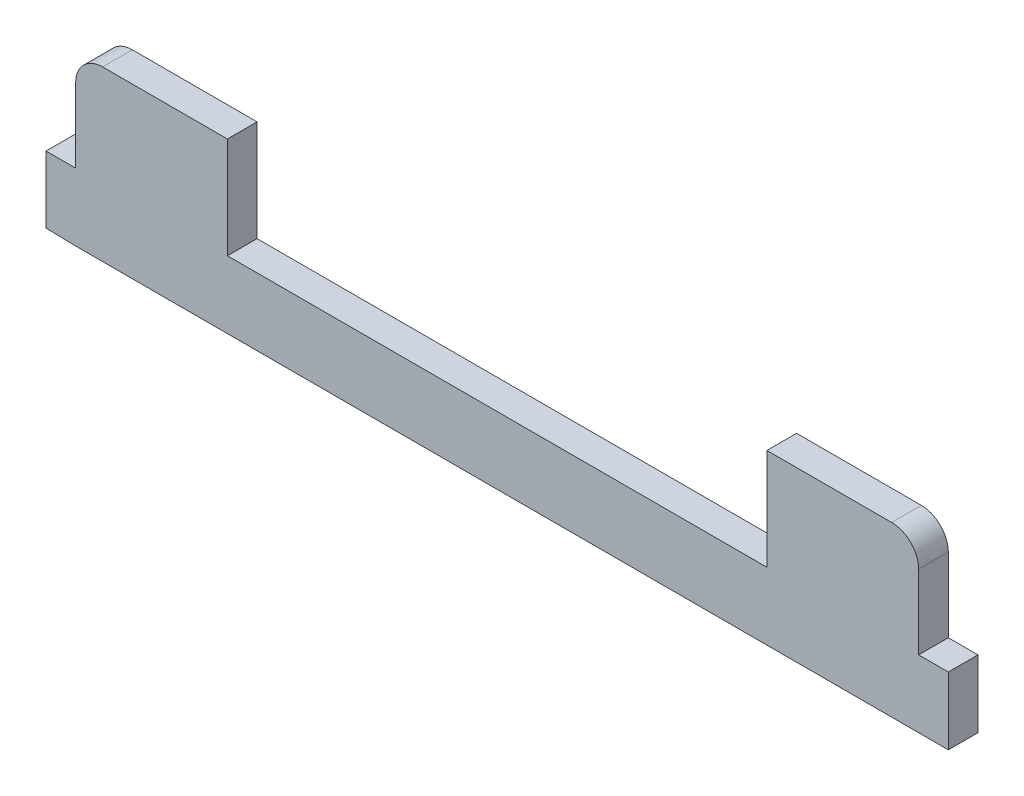
SolidWorks part; units mm, degrees
ref_plane "Front Plane" through (0, 0, 0) normal (0, 0, 1) x (1, 0, 0)
ref_plane "Top Plane" through (0, 0, 0) normal (0, 1, 0) x (1, 0, 0)
ref_plane "Right Plane" through (0, 0, 0) normal (1, 0, 0) x (0, 0, -1)
sketch "Sketch1" plane through (0, 0, 0) normal (0, 0, 1) x (1, 0, 0)
  line L0 (-4.2017, 0) -> (75.1733, 0)
  line L1 (75.1733, 6.35) -> (75.1733, 15.875)
  line L2 (75.1733, 15.875) -> (60.8858, 15.875)
  line L3 (60.8858, 15.875) -> (60.8858, 6.35)
  line L4 (60.8858, 6.35) -> (10.0858, 6.35)
  line L5 (10.0858, 6.35) -> (10.0858, 15.875)
  line L6 (10.0858, 15.875) -> (-4.2017, 15.875)
  line L7 (-4.2017, 15.875) -> (-4.2017, 6.35)
  line L8 (-4.2017, 43.5489) -> (-4.2017, 2.0534) construction
  line L9 (-4.2017, 6.35) -> (-6.9957, 6.35)
  line L10 (-6.9957, 43.5489) -> (-6.9957, 2.0534) construction
  line L11 (-6.9957, 6.35) -> (-6.9957, 0.0621)
  line L12 (-6.9957, 0.0621) -> (-4.2017, 0)
  line L13 (75.1733, 0.6194) -> (75.1733, 26.5797) construction
  line L14 (75.1733, 6.35) -> (77.9673, 6.35)
  line L15 (77.9673, 0.6194) -> (77.9673, 26.5797) construction
  line L16 (77.9673, 6.35) -> (77.9673, 0)
  line L17 (77.9673, -21.7805) -> (77.9673, -5.3322) construction
  line L18 (77.9673, 0) -> (75.1733, 0)
  dimension "D1" = 50.8
  dimension "D2" = 6.35
  dimension "D3" = 9.525
extrude "Boss-Extrude1" add sketch "Sketch1" along normal blind 2.794
fillet "Fillet1" radius 2.54 2 edges at (-4.2017, 15.875, 1.397) (75.1733, 15.875, 1.397)
equation "\"D1@Boss-Extrude1\"=\"thick@assy.sldasm\""
